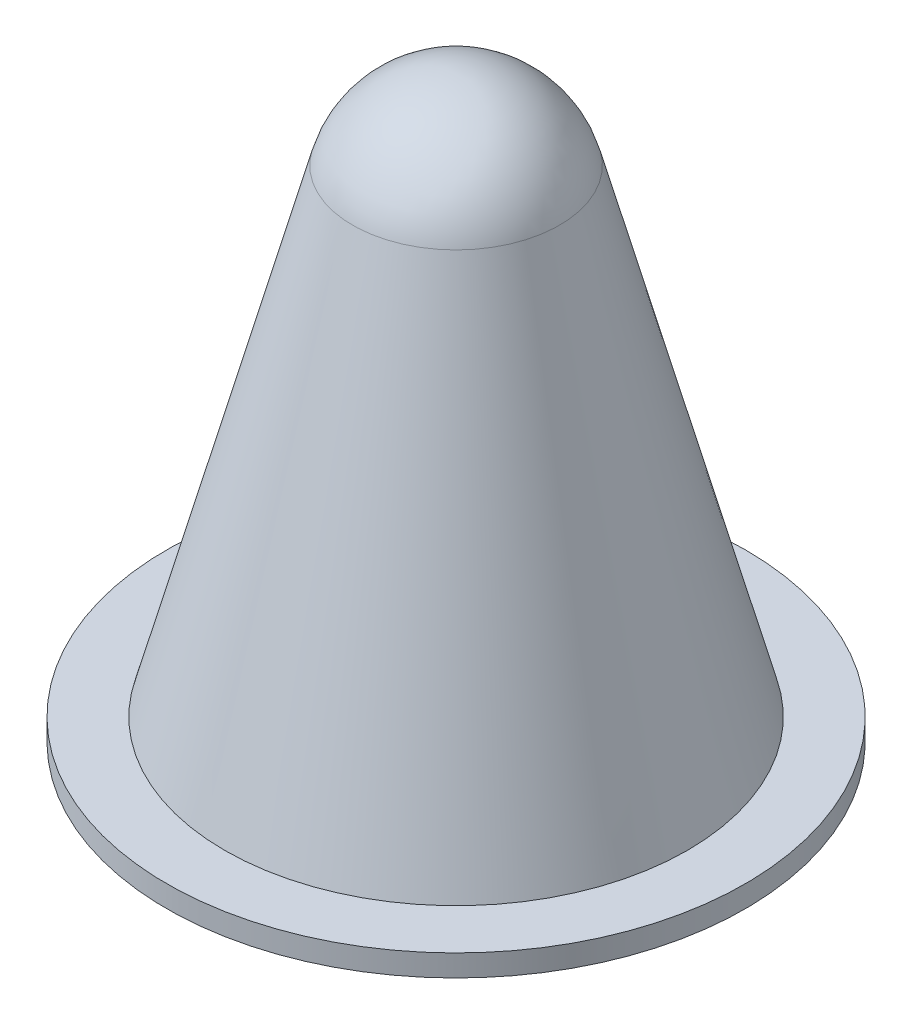
SolidWorks part; units mm, degrees
ref_plane "前视基准面" through (0, 0, 0) normal (0, 0, 1) x (1, 0, 0)
ref_plane "上视基准面" through (0, 0, 0) normal (0, 1, 0) x (1, 0, 0)
ref_plane "右视基准面" through (0, 0, 0) normal (1, 0, 0) x (0, 0, -1)
sketch "草图2" plane through (0, 0, 0) normal (0, 0, 1) x (1, 0, 0)
  line L0 (-14.3101, 3.8344) -> (-32, -62.185)
  line L1 (-32, -62.185) -> (-40, -62.185)
  line L2 (-40, -62.185) -> (-40, -65.185)
  line L3 (-40, -65.185) -> (0, -65.185)
  line L4 (0, -65.185) -> (0, 14.815)
  arc A0 (0, 14.815) -> (-14.3101, 3.8344) centre (0, 0) ccw
  point P8 (-20.2886, 7.7703)
  point P9 (0, 0)
  point P10 (-9.2872, 2.7457)
  dimension "D1" = 40
  dimension "D2" = 80
  dimension "D3" = 3
  dimension "D4" = 8
  dimension "D5" = 75
revolve "旋转1" add sketch "草图2" angle 360 about L4
